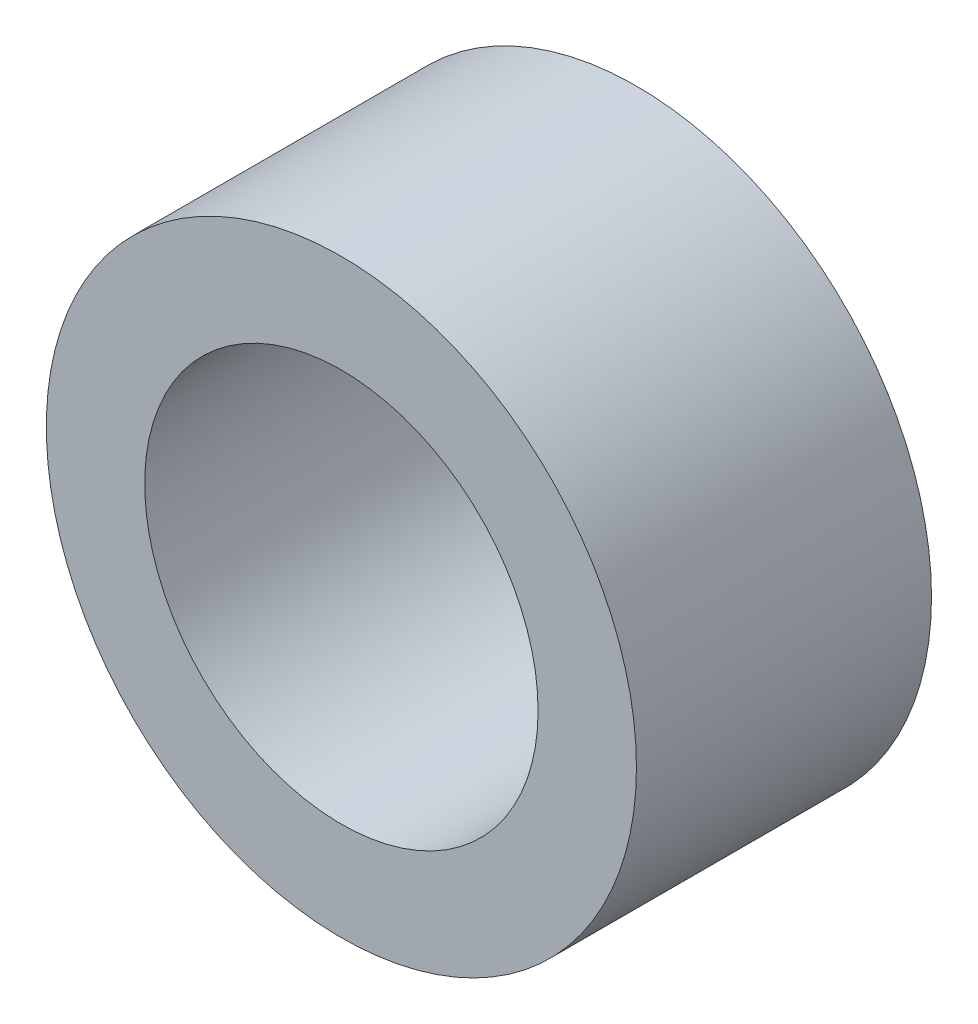
SolidWorks part; units mm, degrees
ref_plane "Front Plane" through (0, 0, 0) normal (0, 0, 1) x (1, 0, 0)
ref_plane "Top Plane" through (0, 0, 0) normal (0, 1, 0) x (1, 0, 0)
ref_plane "Right Plane" through (0, 0, 0) normal (1, 0, 0) x (0, 0, -1)
sketch "Sketch1" plane through (0, 0, 0) normal (0, 0, 1) x (1, 0, 0)
  circle A0 centre (0, 0) radius 3
  circle A1 centre (0, 0) radius 2
  dimension "D1" = 4
  dimension "D2" = 6
extrude "Boss-Extrude1" add sketch "Sketch1" along normal mid plane 3
